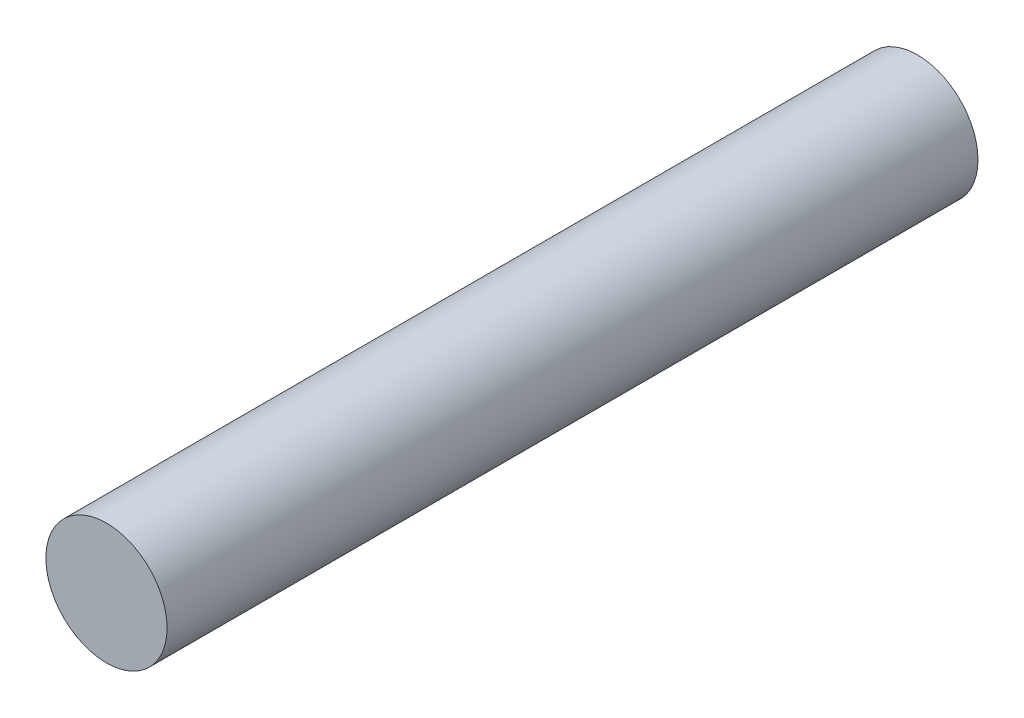
SolidWorks part; units mm, degrees
ref_plane "Front Plane" through (0, 0, 0) normal (0, 0, 1) x (1, 0, 0)
ref_plane "Top Plane" through (0, 0, 0) normal (0, 1, 0) x (1, 0, 0)
ref_plane "Right Plane" through (0, 0, 0) normal (1, 0, 0) x (0, 0, -1)
sketch "Sketch1" plane through (0, 0, 0) normal (0, 0, 1) x (1, 0, 0)
  circle A0 centre (0, 0) radius 25.4
  dimension "D1" = 50.8
extrude "Boss-Extrude1" add sketch "Sketch1" along normal blind 339.852
